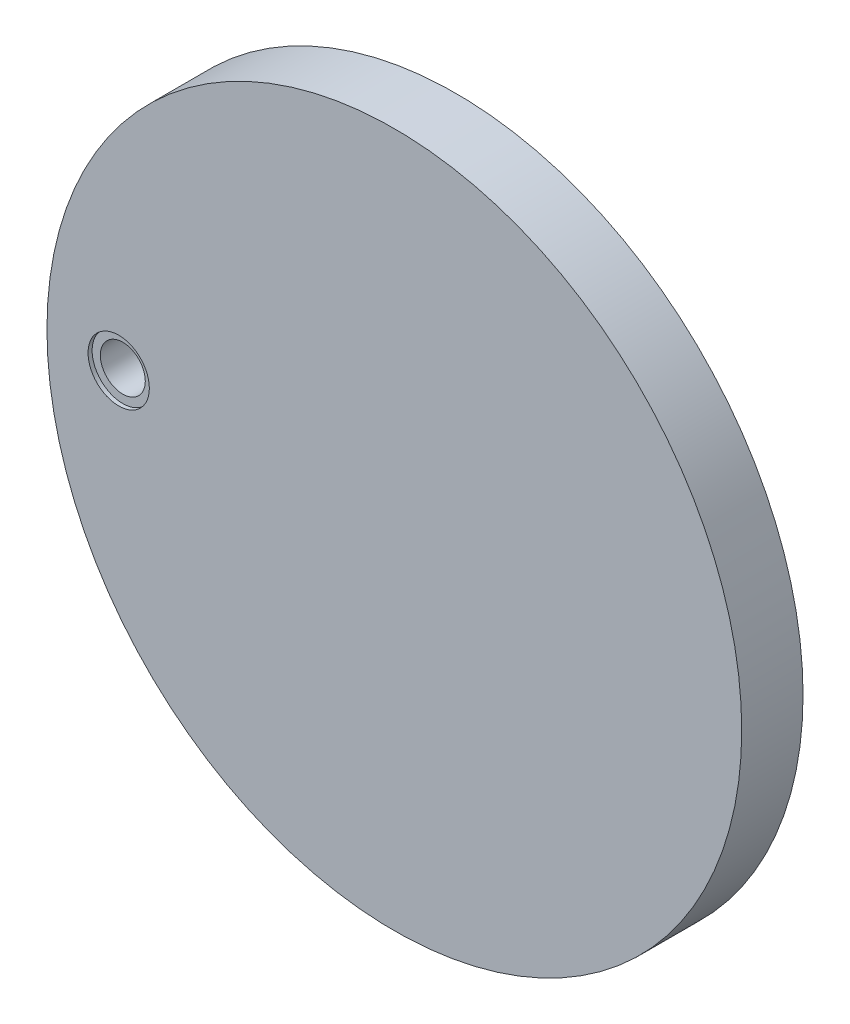
SolidWorks part; units mm, degrees
ref_plane "Plan de face" through (0, 0, 0) normal (0, 0, 1) x (1, 0, 0)
ref_plane "Plan de dessus" through (0, 0, 0) normal (0, 1, 0) x (1, 0, 0)
ref_plane "Plan de droite" through (0, 0, 0) normal (1, 0, 0) x (0, 0, -1)
sketch "Esquisse1" plane through (0, 0, 0) normal (0, 0, 1) x (1, 0, 0)
  line L0 (-180.0737, 0) -> (-45.0737, 0) construction
  circle A0 centre (-112.5737, 0) radius 85
  point P3 (-112.5737, 0)
  dimension "D2" = 170
  dimension "D1" = 135
extrude "Boss.-Extru.1" add sketch "Esquisse1" along normal blind 15
sketch "Esquisse2" plane through (0, 0, 15) normal (0, 0, 1) x (1, 0, 0)
  circle A0 centre (-180.0196, 0) radius 7.5
  point P1 (-180.0196, 0)
extrude "Enlèv. mat.-Extru.1" cut sketch "Esquisse2" against normal blind 1
sketch "Esquisse4" plane through (0, 0, 14) normal (0, 0, 1) x (1, 0, 0)
  circle A0 centre (-180.0106, 0) radius 5.5
  dimension "D1" = 11
extrude "Enlèv. mat.-Extru.2" cut sketch "Esquisse4" against normal blind 15
